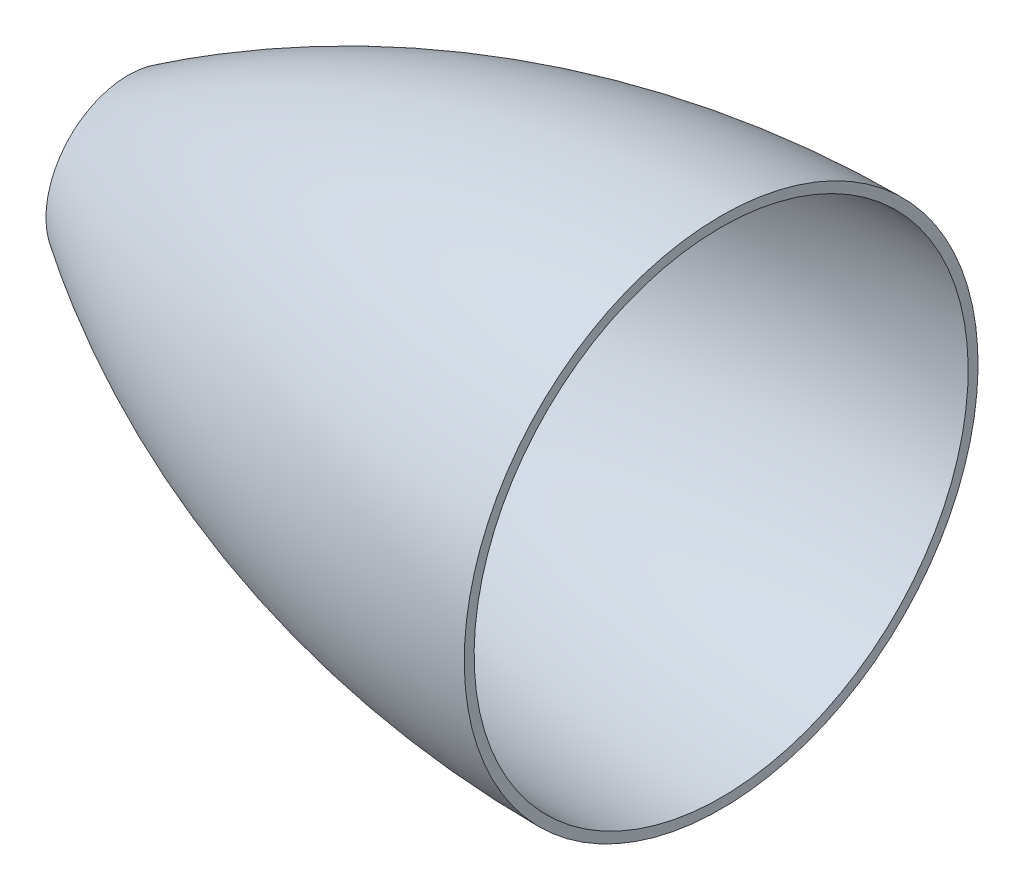
SolidWorks part; units mm, degrees
ref_plane "Front Plane" through (0, 0, 0) normal (0, 0, 1) x (1, 0, 0)
ref_plane "Top Plane" through (0, 0, 0) normal (0, 1, 0) x (1, 0, 0)
ref_plane "Right Plane" through (0, 0, 0) normal (1, 0, 0) x (0, 0, -1)
sketch "Sketch1" plane through (0, 0, 0) normal (0, 0, 1) x (1, 0, 0)
  line L0 (-860.683, 0) -> (-1040.683, 0) construction
  line L5 (-860.683, 78) -> (-860.683, 75)
  line L7 (-995.683, 0) -> (-995.683, 25)
  line L8 (-995.683, 25) -> (-1040.683, 25)
  line L9 (-1030.1884, 28) -> (-992.683, 28)
  line L10 (-1040.683, 0) -> (-1040.683, 25) construction
  line L11 (-1037.683, 0) -> (-1037.683, 23.36) construction
  line L12 (-992.683, 28) -> (-992.683, 0)
  line L13 (-992.683, 0) -> (-995.683, 0)
  arc A0 (-860.683, 78) -> (-1040.683, 25) centre (-860.683, -254.1604) ccw
  arc A1 (-860.683, 75) -> (-1030.1884, 28) centre (-860.683, -254.1604) ccw
  arc A2 (-860.683, 75) -> (-1037.683, 23.36) centre (-860.683, -254.1604) ccw construction
  dimension "D2" = 25
  dimension "D1" = 180
  dimension "D4" = 3
  dimension "D5" = 3
  dimension "D3" = 3
revolve "Revolve1" add sketch "Sketch1" angle 360 about L0
